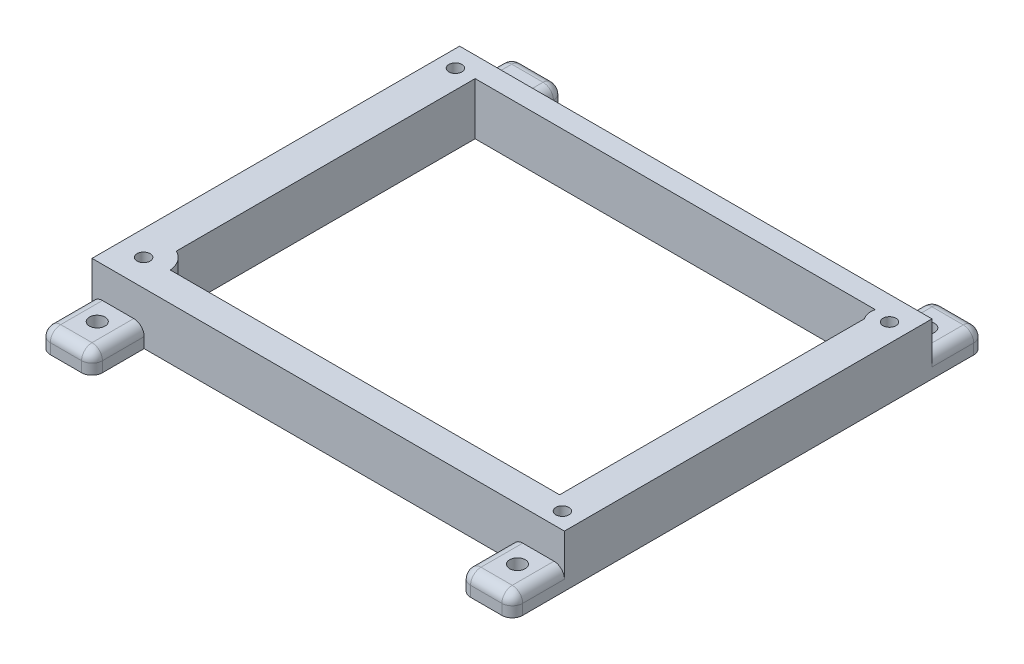
SolidWorks part; units mm, degrees
ref_plane "Front Plane" through (0, 0, 0) normal (0, 0, 1) x (1, 0, 0)
ref_plane "Top Plane" through (0, 0, 0) normal (0, 1, 0) x (1, 0, 0)
ref_plane "Right Plane" through (0, 0, 0) normal (1, 0, 0) x (0, 0, -1)
sketch "Sketch1" plane through (0, 0, 0) normal (0, 1, 0) x (1, 0, 0)
  line L1 (0, 0) -> (-90.58, 0)
  line L2 (0, 0) -> (0, -70.48)
  line L3 (0, -70.48) -> (-90.58, -70.48)
  line L4 (-90.58, 0) -> (-90.58, -70.48)
  line L5 (-83.7, -3.9) -> (-6.49, -3.9)
  line L6 (-83.7, -3.9) -> (-83.7, -64.91)
  line L7 (-83.7, -64.91) -> (-6.49, -64.91)
  line L8 (-6.49, -3.9) -> (-6.49, -64.91)
  circle A0 centre (-87.32, -4.06) radius 1.25
  circle A1 centre (-85.8, -65.37) radius 1.25
  circle A2 centre (-3.505, -67.355) radius 1.25
  circle A3 centre (-3.56, -4.59) radius 1.25
  circle A4 centre (-85.8, -65.37) radius 4.6877
  circle A5 centre (-3.56, -4.59) radius 3.4993
  dimension "D3" = 2.5
  dimension "D4" = 3.9
  dimension "D5" = 5.57
  dimension "D6" = 6.49
  dimension "D16" = 9.3754
  dimension "D1" = 70.48
  dimension "D2" = 90.58
  dimension "D7" = 4.78
  dimension "D8" = 5.11
  dimension "D9" = 3.125
  dimension "D10" = 3.505
  dimension "D11" = 3.56
  dimension "D12" = 4.59
  dimension "D13" = 4.06
  dimension "D14" = 3.26
  dimension "D15" = 6.88
extrude "Boss-Extrude1" add sketch "Sketch1" against normal blind 10 contours L1 L4 L3 L2 A4 L6 L5 L8 L7 A3 A2 A0 | L6 A4 L7 A1 | L7 A4 L6 | L8 A5 L5 A3 | L5 A5 L8
sketch "Sketch2" plane through (0, 0, 70.48) normal (0, 0, 1) x (1, 0, 0)
  line L1 (-90.58, -10) -> (-80.58, -10)
  line L2 (-90.58, -10) -> (-90.58, -6)
  line L3 (-90.58, -6) -> (-80.58, -6)
  line L4 (-80.58, -10) -> (-80.58, -6)
  line L5 (0, -10) -> (-10, -10)
  line L6 (0, -10) -> (0, -6)
  line L7 (0, -6) -> (-10, -6)
  line L8 (-10, -10) -> (-10, -6)
  dimension "D1" = 4
  dimension "D2" = 10
extrude "Boss-Extrude2" add sketch "Sketch2" along normal blind 10
sketch "Sketch3" plane through (0, 0, 0) normal (0, 0, -1) x (-1, 0, 0)
  line L1 (0, -10) -> (10, -10)
  line L2 (0, -10) -> (0, -6)
  line L3 (0, -6) -> (10, -6)
  line L4 (10, -10) -> (10, -6)
  line L5 (90.58, -10) -> (80.58, -10)
  line L6 (90.58, -10) -> (90.58, -6)
  line L7 (90.58, -6) -> (80.58, -6)
  line L8 (80.58, -10) -> (80.58, -6)
  dimension "D1" = 4
  dimension "D2" = 10
extrude "Boss-Extrude3" add sketch "Sketch3" along normal blind 10
fillet "Fillet2" radius 2 8 edges at (0, -8, 80.48) (-10, -8, 80.48) (-80.58, -8, 80.48) (-90.58, -8, 80.48) (-90.58, -8, -10) (-80.58, -8, -10) (0, -8, -10) (-10, -8, -10)
fillet "Fillet3" radius 2 20 edges at (0, -6, -4) (-0.5858, -6, -9.4142) (-5, -6, -10) (-9.4142, -6, -9.4142) (-80.58, -6, -4) (-81.1658, -6, -9.4142) (-85.58, -6, -10) (-89.9942, -6, -9.4142) (-90.58, -6, 74.48) (-89.9942, -6, 79.8942) (-85.58, -6, 80.48) (-81.1658, -6, 79.8942) (-10, -6, 74.48) (-9.4142, -6, 79.8942) (-5, -6, 80.48) (-0.5858, -6, 79.8942) (-10, -6, -4) (-90.58, -6, -4) (-80.58, -6, 74.48) (0, -6, 74.48)
sketch "Sketch4" plane through (0, -6, 0) normal (0, 1, 0) x (1, 0, 0)
  line L0 (-8, 8) -> (-8, 0) construction
  line L1 (-88.58, 8) -> (-88.58, 0) construction
  line L2 (-2, 8) -> (-8, 8) construction
  line L3 (-8, -78.48) -> (-2, -78.48) construction
  circle A0 centre (-5, 4) radius 1.5
  circle A1 centre (-5, -74.48) radius 1.5
  circle A2 centre (-85.58, -74.48) radius 1.5
  circle A3 centre (-85.58, 4) radius 1.5
  point P8 (0, 0)
  point P9 (0, 0)
  point P10 (0, 0)
  point P11 (0, 0)
  point P12 (0, 0)
  point P15 (0, 0)
  dimension "D1" = 3
  dimension "D2" = 3
  dimension "D3" = 3
  dimension "D4" = 4
  dimension "D5" = 4
extrude "Cut-Extrude1" cut sketch "Sketch4" against normal up to next
